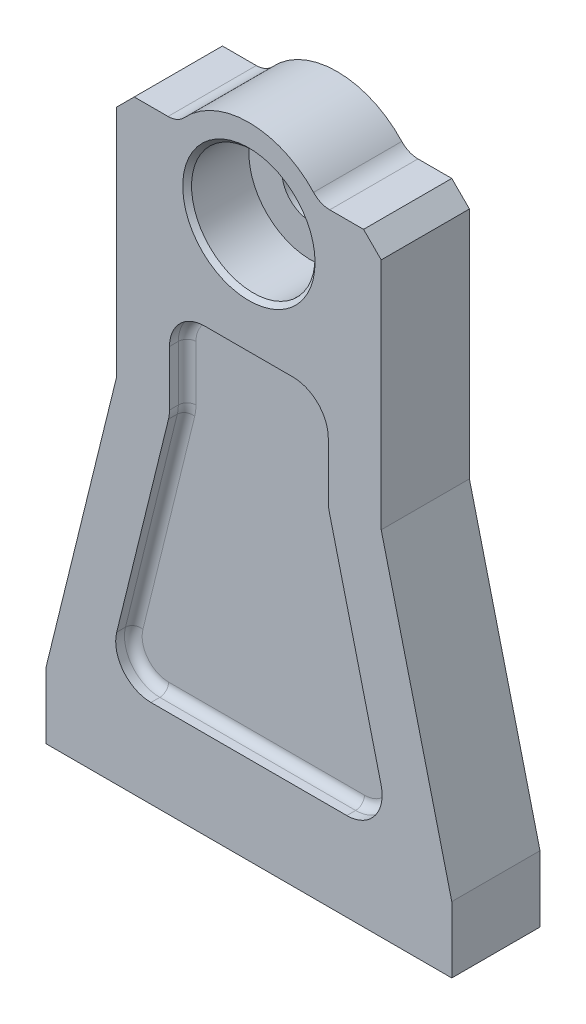
SolidWorks part; units mm, degrees
ref_plane "Front Plane" through (0, 0, 0) normal (0, 0, 1) x (1, 0, 0)
ref_plane "Top Plane" through (0, 0, 0) normal (0, 1, 0) x (1, 0, 0)
ref_plane "Right Plane" through (0, 0, 0) normal (1, 0, 0) x (0, 0, -1)
sketch "Sketch1" plane through (0, 0, 0) normal (0, 0, 1) x (1, 0, 0)
  line L0 (-46, 0) -> (46, 0)
  line L1 (46, 0) -> (46, 15)
  line L2 (46, 15) -> (30, 80)
  line L3 (30, 80) -> (30, 137)
  line L4 (30, 137) -> (16, 137)
  line L5 (0, 0) -> (0, 77.4086) construction
  line L6 (-30, 137) -> (-16, 137)
  line L7 (-30, 80) -> (-30, 137)
  line L8 (-46, 15) -> (-30, 80)
  line L9 (-46, 0) -> (-46, 15)
  circle A0 centre (0, 125) radius 6.5
  arc A1 (16, 137) -> (-16, 137) centre (0, 125) ccw
  dimension "D1" = 40
  dimension "D2" = 13
  dimension "D3" = 125
  dimension "D4" = 46
  dimension "D5" = 15
  dimension "D6" = 65
  dimension "D7" = 12
  dimension "D8" = 57
  dimension "D9" = 30
extrude "Boss-Extrude1" add sketch "Sketch1" along normal mid plane 20
sketch "Sketch2" plane through (0, 0, 10) normal (0, 0, 1) x (1, 0, 0)
  circle A0 centre (0, 125) radius 14
  dimension "D1" = 28
extrude "Cut-Extrude1" cut sketch "Sketch2" against normal blind 14
chamfer "Chamfer1" distance 1 angle 45 1 edges at (14, 125, 10)
chamfer "Chamfer2" distance 4 angle 45 2 edges at (-30, 137, 0) (30, 137, 0)
fillet "Fillet1" radius 5 2 edges at (-16, 137, 0) (16, 137, 0)
sketch "Sketch3" plane through (0, 0, 10) normal (0, 0, 1) x (1, 0, 0)
  line L7 (-18, 133) -> (-18, 78.5448)
  line L8 (-18, 78.5448) -> (-34.3478, 12.1318)
  line L9 (-18, 92) -> (-18, 79.5149)
  line L10 (-18.2319, 77.6028) -> (-29.9711, 29.9122)
  line L13 (-10, 100) -> (10, 100)
  line L14 (34.3478, 12.1318) -> (18, 78.5448)
  line L15 (18, 78.5448) -> (18, 133)
  line L16 (29.9711, 29.9122) -> (18.2319, 77.6028)
  line L17 (18, 79.5149) -> (18, 92)
  line L18 (-46, 20) -> (46, 20)
  line L19 (-22.203, 20) -> (22.203, 20)
  line L20 (-46, 0) -> (46, 0) construction
  arc A0 (18.2319, 77.6028) -> (18, 79.5149) centre (26, 79.5149) cw
  arc A1 (18, 92) -> (10, 100) centre (10, 92) ccw
  arc A2 (-18, 92) -> (-10, 100) centre (-10, 92) cw
  arc A3 (-18, 79.5149) -> (-18.2319, 77.6028) centre (-26, 79.5149) cw
  arc A4 (29.9711, 29.9122) -> (22.203, 20) centre (22.203, 28) cw
  arc A5 (-22.203, 20) -> (-29.9711, 29.9122) centre (-22.203, 28) cw
  dimension "D5" = 8
  dimension "D4" = 100
  dimension "D1" = 12
  dimension "D2" = 12
  dimension "D3" = 20
extrude "Cut-Extrude2" cut sketch "Sketch3" against normal blind 4
fillet "Fillet2" radius 2 12 edges at (24.1015, 53.7575, 6) (28.4997, 23.0653, 6) (0, 20, 6) (-28.4997, 23.0653, 6) (-24.1015, 53.7575, 6) (-18.0582, 78.5519, 6) (-18, 85.7575, 6) (-15.6569, 97.6569, 6) (0, 100, 6) (15.6569, 97.6569, 6) (18, 85.7575, 6) (18.0582, 78.5519, 6)
mirror "Mirror1" about plane through (0, 0, 0) normal (0, 0, 1) of "Fillet2", "Cut-Extrude2"
hole_wizard "M10x1.25 Tapped Hole2" positions "Sketch7" profile "Sketch8" tap size "M10x1.25" standard "ISO"
sketch "Sketch7" plane through (0, 0, 0) normal (0, -1, 0) x (-1, 0, 0)
  line L0 (-46, -10) -> (-46, 10) construction
  point P0 (-30, 0)
  point P2 (30, 0)
  dimension "D1" = 60
  dimension "D2" = 16
  dimension "D3" = 10
sketch "Sketch8" plane through (30, 0, 0) normal (1, 0, 0) x (0, 0, -1)
  line L0 (0, 0) -> (0, 22.6438)
  line L1 (0, 22.6438) -> (4.4, 20)
  line L2 (4.4, 20) -> (4.4, 0.625)
  line L3 (4.4, 0.625) -> (5.025, 0)
  line L5 (5.025, 0) -> (0, 0)
  line L6 (-4.4, 0.625) -> (-5.025, 0) construction
  line L10 (0, 22.6438) -> (-4.4, 20) construction
  line L11 (0, -6.35) -> (0, 107.95) construction
  dimension "Tap Drill Dia." = 8.8
  dimension "Tap Drill Depth" = 20
  dimension "Near C'Sink Dia." = 10.05
  dimension "Near C'Sink Angle" = 90
  dimension "Drill Angle" = 118
cosmetic thread "Hole Thread3" parameters "D1"=20, "D2"=10
cosmetic thread "Hole Thread4" parameters "D1"=20, "D2"=10
